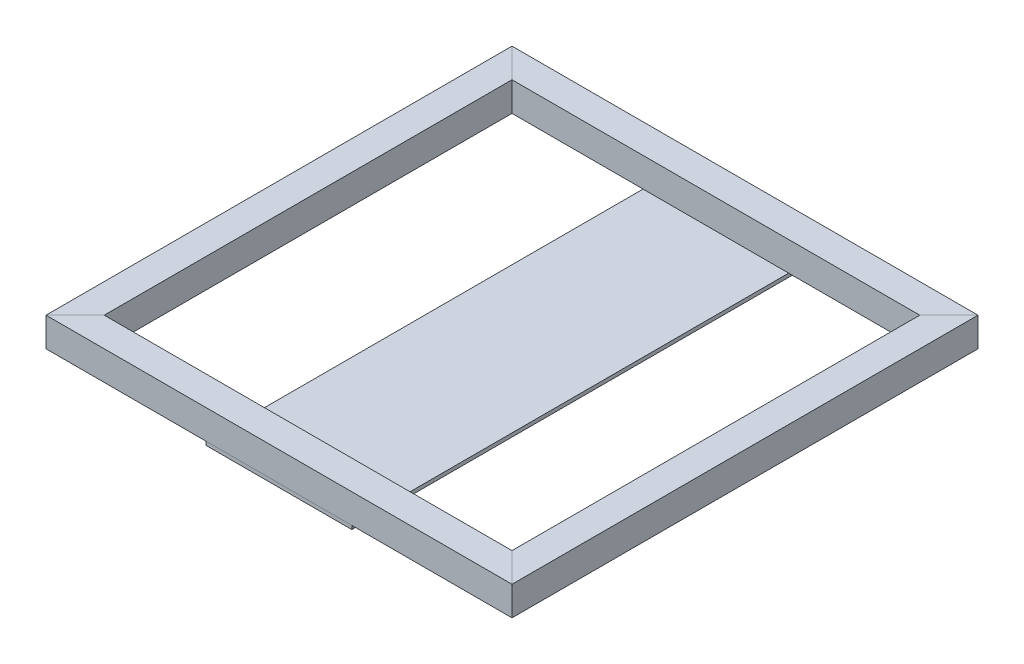
SolidWorks part; units mm, degrees
ref_plane "Alzado" through (0, 0, 0) normal (0, 0, 1) x (1, 0, 0)
ref_plane "Planta" through (0, 0, 0) normal (0, 1, 0) x (1, 0, 0)
ref_plane "Vista lateral" through (0, 0, 0) normal (1, 0, 0) x (0, 0, -1)
sketch "Croquis1" plane through (0, 0, 0) normal (0, 1, 0) x (1, 0, 0)
  line L1 (-150, 150) -> (150, 150)
  line L2 (-150, 150) -> (-150, -150)
  line L3 (-150, -150) -> (150, -150)
  line L4 (150, 150) -> (150, -150)
  line L5 (-150, 150) -> (150, -150) construction
  line L6 (-150, -150) -> (150, 150) construction
  point P0 (0, 0)
  dimension "D1" = 300
  dimension "D2" = 300
other "Tubo cuadrado 20 X 20 X 2(2)"
ref_plane "Plano2" through (-150, 0, -150) normal (0, 0, 1) x (1, 0, 0)
sketch "Sketch1" plane through (-150, 0, -150) normal (0, 0, 1) x (1, 0, 0)
  line L2 (10, 10) -> (-10, 10)
  line L3 (10, 10) -> (10, -10)
  line L4 (10, -10) -> (-10, -10)
  line L5 (-10, 10) -> (-10, -10)
  line L6 (10, 10) -> (-10, -10) construction
  line L7 (10, -10) -> (-10, 10) construction
  line L8 (-8, 8) -> (8, 8)
  line L9 (-8, 8) -> (-8, -8)
  line L10 (-8, -8) -> (8, -8)
  line L11 (8, 8) -> (8, -8)
  line L12 (-8, 8) -> (8, -8) construction
  line L13 (-8, -8) -> (8, 8) construction
  point P0 (0, 0)
  point P5 (0, 0)
  dimension "D1" = 20
  dimension "D2" = 20
  dimension "D3" = 2
ref_plane "Plano3" through (0, -10, 0) normal (0, 1, 0) x (1, 0, 0)
sketch "Croquis3" plane through (0, -10, 0) normal (0, 1, 0) x (1, 0, 0)
  line L0 (160, -160) -> (-160, -160) construction
  line L1 (-50, 160) -> (50, 160)
  line L2 (-50, 160) -> (-50, -160)
  line L3 (-50, -160) -> (50, -160)
  line L4 (50, 160) -> (50, -160)
  line L5 (-50, 160) -> (50, -160) construction
  line L6 (-50, -160) -> (50, 160) construction
  point P0 (0, 0)
  dimension "D1" = 100
extrude "Saliente-Extruir1" add sketch "Croquis3" against normal blind 2.5 separate body
